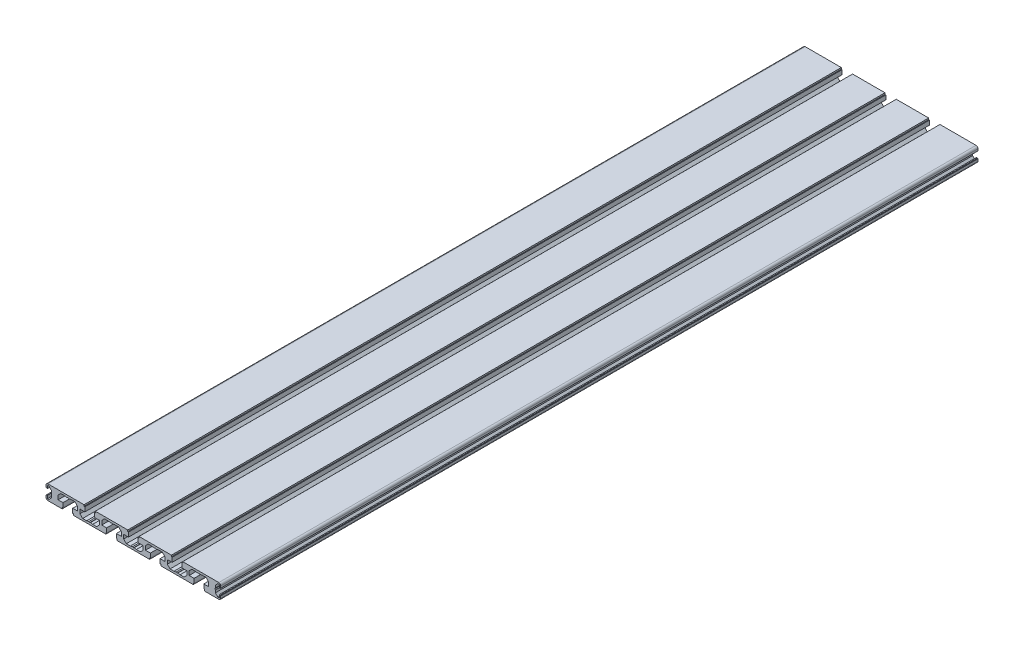
SolidWorks part; units mm, degrees
material "3.1355 (EN-AW 2024)"
ref_plane "Спереди" through (0, 0, 0) normal (0, 0, 1) x (1, 0, 0)
ref_plane "Сверху" through (0, 0, 0) normal (0, 1, 0) x (1, 0, 0)
ref_plane "Справа" through (0, 0, 0) normal (1, 0, 0) x (0, 0, -1)
sketch "Model" plane through (0, 0, 0) normal (0, 0, 1) x (1, 0, 0)
  line L0 (-87.1, -7.5) -> (-72.4, -7.5)
  line L1 (-72.4, -7.5) -> (-72.4, -6)
  line L2 (-72.4, -6) -> (-71.6, -6)
  line L3 (-71.6, -6) -> (-71.6, -1.5)
  line L4 (-71.6, -1.5) -> (-76.65, -1.5)
  line L5 (-76.65, -1.5) -> (-76.65, 2.7)
  line L6 (-76.65, 2.7) -> (-73.85, 5.5)
  line L7 (-73.85, 5.5) -> (-69.7225, 5.5)
  line L8 (-67.5, 5.0406) -> (-66.6, 5.5602)
  line L9 (-66.6, 5.5602) -> (-65.7, 5.0406)
  line L10 (-63.4775, 5.5) -> (-59.35, 5.5)
  line L11 (-59.35, 5.5) -> (-56.55, 2.7)
  line L12 (-56.55, 2.7) -> (-56.55, -1.5)
  line L13 (-56.55, -1.5) -> (-61.6, -1.5)
  line L14 (-61.6, -1.5) -> (-61.6, -6)
  line L15 (-61.6, -6) -> (-60.8, -6)
  line L16 (-60.8, -6) -> (-60.8, -7.5)
  line L17 (-60.8, -7.5) -> (-27.4, -7.5)
  line L18 (-27.4, -7.5) -> (-27.4, -6)
  line L19 (-27.4, -6) -> (-26.6, -6)
  line L20 (-26.6, -6) -> (-26.6, -1.5)
  line L21 (-26.6, -1.5) -> (-31.65, -1.5)
  line L22 (-31.65, -1.5) -> (-31.65, 2.7)
  line L23 (-31.65, 2.7) -> (-28.85, 5.5)
  line L24 (-28.85, 5.5) -> (-24.7225, 5.5)
  line L25 (-22.5, 5.0406) -> (-21.6, 5.5602)
  line L26 (-21.6, 5.5602) -> (-20.7, 5.0406)
  line L27 (-18.4775, 5.5) -> (-14.35, 5.5)
  line L28 (-14.35, 5.5) -> (-11.55, 2.7)
  line L29 (-11.55, 2.7) -> (-11.55, -1.5)
  line L30 (-11.55, -1.5) -> (-16.6, -1.5)
  line L31 (-16.6, -1.5) -> (-16.6, -6)
  line L32 (-16.6, -6) -> (-15.8, -6)
  line L33 (-15.8, -6) -> (-15.8, -7.5)
  line L34 (-15.8, -7.5) -> (17.6, -7.5)
  line L35 (17.6, -7.5) -> (17.6, -6)
  line L36 (17.6, -6) -> (18.4, -6)
  line L37 (18.4, -6) -> (18.4, -1.5)
  line L38 (18.4, -1.5) -> (13.35, -1.5)
  line L39 (13.35, -1.5) -> (13.35, 2.7)
  line L40 (13.35, 2.7) -> (16.15, 5.5)
  line L41 (16.15, 5.5) -> (20.2775, 5.5)
  line L42 (22.5, 5.0406) -> (23.4, 5.5602)
  line L43 (23.4, 5.5602) -> (24.3, 5.0406)
  line L44 (26.5225, 5.5) -> (30.65, 5.5)
  line L45 (30.65, 5.5) -> (33.45, 2.7)
  line L46 (33.45, 2.7) -> (33.45, -1.5)
  line L47 (33.45, -1.5) -> (28.4, -1.5)
  line L48 (28.4, -1.5) -> (28.4, -6)
  line L49 (28.4, -6) -> (29.2, -6)
  line L50 (29.2, -6) -> (29.2, -7.5)
  line L51 (29.2, -7.5) -> (62.6, -7.5)
  line L52 (62.6, -7.5) -> (62.6, -6)
  line L53 (62.6, -6) -> (63.4, -6)
  line L54 (63.4, -6) -> (63.4, -1.5)
  line L55 (63.4, -1.5) -> (58.35, -1.5)
  line L56 (58.35, -1.5) -> (58.35, 2.7)
  line L57 (58.35, 2.7) -> (61.15, 5.5)
  line L58 (61.15, 5.5) -> (65.2775, 5.5)
  line L59 (67.5, 5.0406) -> (68.4, 5.5602)
  line L60 (68.4, 5.5602) -> (69.3, 5.0406)
  line L61 (71.5225, 5.5) -> (75.65, 5.5)
  line L62 (75.65, 5.5) -> (78.45, 2.7)
  line L63 (78.45, 2.7) -> (78.45, -1.5)
  line L64 (78.45, -1.5) -> (73.4, -1.5)
  line L65 (73.4, -1.5) -> (73.4, -6)
  line L66 (73.4, -6) -> (74.2, -6)
  line L67 (74.2, -6) -> (74.2, -7.5)
  line L68 (74.2, -7.5) -> (88.9, -7.5)
  line L69 (90.9, -5.5) -> (90.9, -3.5)
  line L70 (90.9, -3.5) -> (90.4, -3.5)
  line L71 (90.4, -3.5) -> (90.4, -3)
  line L72 (90.4, -3) -> (89.4, -3)
  line L73 (89.4, -3) -> (89.4, -6)
  line L74 (89.4, -6) -> (87.95, -6)
  line L75 (87.95, -6) -> (85.4, -3.45)
  line L76 (85.4, -3.45) -> (85.4, -0.9196)
  line L77 (85.4, -0.9196) -> (84.8691, 0)
  line L78 (84.8691, 0) -> (85.4, 0.9196)
  line L79 (85.4, 0.9196) -> (85.4, 3.45)
  line L80 (85.4, 3.45) -> (87.95, 6)
  line L81 (87.95, 6) -> (89.4, 6)
  line L82 (89.4, 6) -> (89.4, 3)
  line L83 (89.4, 3) -> (90.4, 3)
  line L84 (90.4, 3) -> (90.4, 3.5)
  line L85 (90.4, 3.5) -> (90.9, 3.5)
  line L86 (90.9, 3.5) -> (90.9, 5.5)
  line L87 (88.9, 7.5) -> (51.7, 7.5)
  line L88 (51.7, 7.5) -> (51.7, 6)
  line L89 (51.7, 6) -> (50.9, 6)
  line L90 (50.9, 6) -> (50.9, 1.5)
  line L91 (50.9, 1.5) -> (55.95, 1.5)
  line L92 (55.95, 1.5) -> (55.95, -2.7)
  line L93 (55.95, -2.7) -> (53.15, -5.5)
  line L94 (53.15, -5.5) -> (49.0225, -5.5)
  line L95 (46.8, -5.0406) -> (45.9, -5.5602)
  line L96 (45.9, -5.5602) -> (45, -5.0406)
  line L97 (42.7775, -5.5) -> (38.65, -5.5)
  line L98 (38.65, -5.5) -> (35.85, -2.7)
  line L99 (35.85, -2.7) -> (35.85, 1.5)
  line L100 (35.85, 1.5) -> (40.9, 1.5)
  line L101 (40.9, 1.5) -> (40.9, 6)
  line L102 (40.9, 6) -> (40.1, 6)
  line L103 (40.1, 6) -> (40.1, 7.5)
  line L104 (40.1, 7.5) -> (6.7, 7.5)
  line L105 (6.7, 7.5) -> (6.7, 6)
  line L106 (6.7, 6) -> (5.9, 6)
  line L107 (5.9, 6) -> (5.9, 1.5)
  line L108 (5.9, 1.5) -> (10.95, 1.5)
  line L109 (10.95, 1.5) -> (10.95, -2.7)
  line L110 (10.95, -2.7) -> (8.15, -5.5)
  line L111 (8.15, -5.5) -> (4.0225, -5.5)
  line L112 (1.8, -5.0406) -> (0.9, -5.5602)
  line L113 (0.9, -5.5602) -> (0, -5.0406)
  line L114 (-2.2225, -5.5) -> (-6.35, -5.5)
  line L115 (-6.35, -5.5) -> (-9.15, -2.7)
  line L116 (-9.15, -2.7) -> (-9.15, 1.5)
  line L117 (-9.15, 1.5) -> (-4.1, 1.5)
  line L118 (-4.1, 1.5) -> (-4.1, 6)
  line L119 (-4.1, 6) -> (-4.9, 6)
  line L120 (-4.9, 6) -> (-4.9, 7.5)
  line L121 (-4.9, 7.5) -> (-38.3, 7.5)
  line L122 (-38.3, 7.5) -> (-38.3, 6)
  line L123 (-38.3, 6) -> (-39.1, 6)
  line L124 (-39.1, 6) -> (-39.1, 1.5)
  line L125 (-39.1, 1.5) -> (-34.05, 1.5)
  line L126 (-34.05, 1.5) -> (-34.05, -2.7)
  line L127 (-34.05, -2.7) -> (-36.85, -5.5)
  line L128 (-36.85, -5.5) -> (-40.9775, -5.5)
  line L129 (-43.2, -5.0406) -> (-44.1, -5.5602)
  line L130 (-44.1, -5.5602) -> (-45, -5.0406)
  line L131 (-47.2225, -5.5) -> (-51.35, -5.5)
  line L132 (-51.35, -5.5) -> (-54.15, -2.7)
  line L133 (-54.15, -2.7) -> (-54.15, 1.5)
  line L134 (-54.15, 1.5) -> (-49.1, 1.5)
  line L135 (-49.1, 1.5) -> (-49.1, 6)
  line L136 (-49.1, 6) -> (-49.9, 6)
  line L137 (-49.9, 6) -> (-49.9, 7.5)
  line L138 (-49.9, 7.5) -> (-87.1, 7.5)
  line L139 (-89.1, 5.5) -> (-89.1, 3.5)
  line L140 (-89.1, 3.5) -> (-88.6, 3.5)
  line L141 (-88.6, 3.5) -> (-88.6, 3)
  line L142 (-88.6, 3) -> (-87.6, 3)
  line L143 (-87.6, 3) -> (-87.6, 6)
  line L144 (-87.6, 6) -> (-86.15, 6)
  line L145 (-86.15, 6) -> (-83.6, 3.45)
  line L146 (-83.6, 3.45) -> (-83.6, -3.45)
  line L147 (-83.6, -3.45) -> (-86.15, -6)
  line L148 (-86.15, -6) -> (-87.6, -6)
  line L149 (-87.6, -6) -> (-87.6, -3)
  line L150 (-87.6, -3) -> (-88.6, -3)
  line L151 (-88.6, -3) -> (-88.6, -3.5)
  line L152 (-88.6, -3.5) -> (-89.1, -3.5)
  line L153 (-89.1, -3.5) -> (-89.1, -5.5)
  arc A0 (-69.7225, 5.5) -> (-67.5, 5.0406) centre (-66.6, 15) ccw
  arc A1 (-65.7, 5.0406) -> (-63.4775, 5.5) centre (-66.6, 15) ccw
  arc A2 (-24.7225, 5.5) -> (-22.5, 5.0406) centre (-21.6, 15) ccw
  arc A3 (-20.7, 5.0406) -> (-18.4775, 5.5) centre (-21.6, 15) ccw
  arc A4 (20.2775, 5.5) -> (22.5, 5.0406) centre (23.4, 15) ccw
  arc A5 (24.3, 5.0406) -> (26.5225, 5.5) centre (23.4, 15) ccw
  arc A6 (65.2775, 5.5) -> (67.5, 5.0406) centre (68.4, 15) ccw
  arc A7 (69.3, 5.0406) -> (71.5225, 5.5) centre (68.4, 15) ccw
  arc A8 (88.9, -7.5) -> (90.9, -5.5) centre (88.9, -5.5) ccw
  arc A9 (90.9, 5.5) -> (88.9, 7.5) centre (88.9, 5.5) ccw
  arc A10 (49.0225, -5.5) -> (46.8, -5.0406) centre (45.9, -15) ccw
  arc A11 (45, -5.0406) -> (42.7775, -5.5) centre (45.9, -15) ccw
  arc A12 (4.0225, -5.5) -> (1.8, -5.0406) centre (0.9, -15) ccw
  arc A13 (0, -5.0406) -> (-2.2225, -5.5) centre (0.9, -15) ccw
  arc A14 (-40.9775, -5.5) -> (-43.2, -5.0406) centre (-44.1, -15) ccw
  arc A15 (-45, -5.0406) -> (-47.2225, -5.5) centre (-44.1, -15) ccw
  arc A16 (-87.1, 7.5) -> (-89.1, 5.5) centre (-87.1, 5.5) ccw
  arc A17 (-89.1, -5.5) -> (-87.1, -7.5) centre (-87.1, -5.5) ccw
extrude "База" add sketch "Model" along normal mid plane 780
